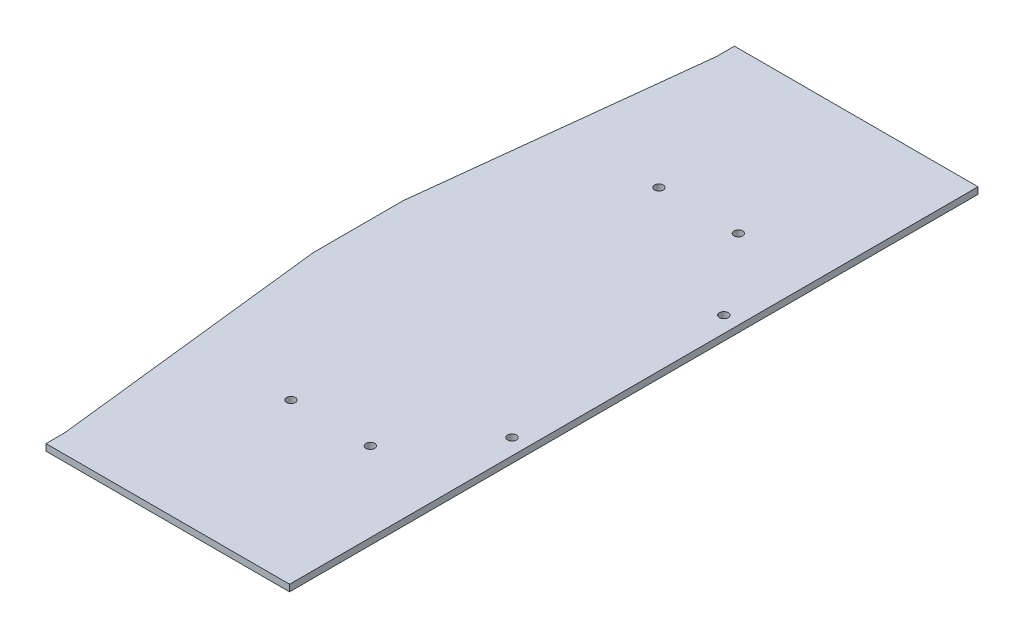
SolidWorks part; units mm, degrees
ref_plane "前视基准面" through (0, 0, 0) normal (0, 0, 1) x (1, 0, 0)
ref_plane "上视基准面" through (0, 0, 0) normal (0, 1, 0) x (1, 0, 0)
ref_plane "右视基准面" through (0, 0, 0) normal (1, 0, 0) x (0, 0, -1)
sketch "草图1" plane through (0, 0, 0) normal (0, 1, 0) x (1, 0, 0)
  line L0 (85.2736, -129.2943) -> (135.1202, -129.2943)
  line L1 (31.1202, 17.7057) -> (31.1202, -16.2943)
  line L2 (31.1202, -16.2943) -> (43.1202, -122.2943)
  line L3 (31.1202, 0.7057) -> (131.5323, 0.7057) construction
  line L4 (43.1202, -122.2943) -> (43.1202, -129.2943)
  line L5 (43.1202, -129.2943) -> (85.2736, -129.2943)
  line L6 (135.1202, -129.2943) -> (135.1202, 130.7057)
  line L7 (85.2736, 130.7057) -> (135.1202, 130.7057)
  line L8 (43.1202, 130.7057) -> (85.2736, 130.7057)
  line L9 (43.1202, 123.7057) -> (43.1202, 130.7057)
  line L10 (31.1202, 17.7057) -> (43.1202, 123.7057)
  circle A0 centre (105.1202, 70.2057) radius 1.65
  circle A1 centre (75.1202, 70.2057) radius 1.65
  circle A2 centre (75.1202, -68.7943) radius 1.65
  circle A3 centre (105.1202, -68.7943) radius 1.65
  circle A4 centre (129.1202, 40.7057) radius 1.65
  circle A5 centre (129.1202, -39.2943) radius 1.65
  dimension "D1" = 139
  dimension "D4" = 30
  dimension "D8" = 3.3
  dimension "D9" = 3.3
  dimension "D10" = 30
  dimension "D11" = 3.3
  dimension "D12" = 6
  dimension "D13" = 80
  dimension "D2" = 7
  dimension "D3" = 260
  dimension "D5" = 92
  dimension "D6" = 34
  dimension "D7" = 12
extrude "凸台-拉伸1" add sketch "草图1" along normal blind 2.5
